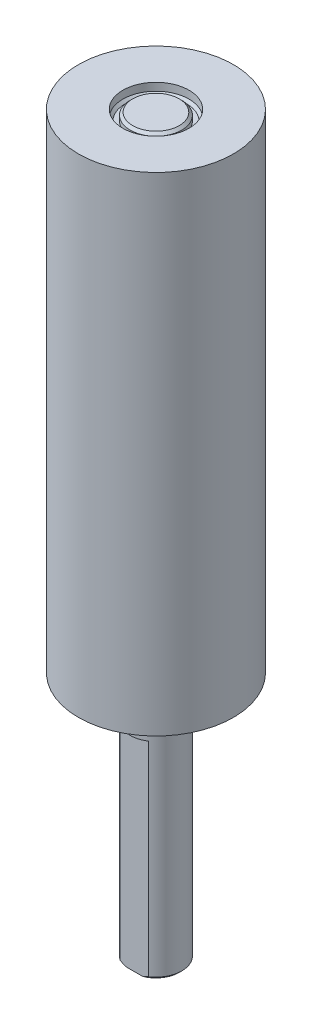
SolidWorks part; units mm, degrees
ref_plane "Alzado" through (0, 0, 0) normal (0, 0, 1) x (1, 0, 0)
ref_plane "Planta" through (0, 0, 0) normal (0, 1, 0) x (1, 0, 0)
ref_plane "Vista lateral" through (0, 0, 0) normal (1, 0, 0) x (0, 0, -1)
ref_plane "Plano4" through (0, 0, 0) normal (0, 0, -1) x (-1, 0, 0)
sketch "Croquis1" plane through (0, 0, 0) normal (0, 0, -1) x (-1, 0, 0)
  line L0 (-7.5, -8) -> (0, -8)
  line L1 (0, -8) -> (0, 39.25)
  line L2 (0, 39.25) -> (-7.5, 39.25)
  line L3 (-7.5, 39.25) -> (-7.5, -8)
  line L4 (0, -8) -> (0, 39.25) construction
revolve "Revolución1" add sketch "Croquis1" angle 360 about L4
sketch "Croquis2" plane through (0, -8, 0) normal (0, -1, 0) x (1, 0, 0)
  circle A0 centre (0, 0) radius 3.2
extrude "Saliente-Extruir1" add sketch "Croquis2" along normal blind 1
sketch "Croquis3" plane through (0, -9, 0) normal (0, -1, 0) x (1, 0, 0)
  circle A0 centre (0, 0) radius 2.5
extrude "Saliente-Extruir2" add sketch "Croquis3" along normal blind 23
sketch "Croquis4" plane through (0, -32, 0) normal (0, -1, 0) x (1, 0, 0)
  line L0 (-1.3565, 2.1) -> (1.3565, 2.1)
  arc A0 (1.3565, 2.1) -> (-1.3565, 2.1) centre (0, 0) ccw
extrude "Cortar-Extruir1" cut sketch "Croquis4" against normal blind 20
hole_wizard "Diámetro de taladro Ø6.4 (6.4)1" positions "Croquis6" profile "Croquis5" hole size "Ø6.4" standard "Ansi Metric"
sketch "Croquis6" plane through (0, 39.25, 0) normal (0, 1, 0) x (1, 0, 0)
  point P0 (0, 0)
sketch "Croquis5" plane through (0, 39.25, 0) normal (1, 0, 0) x (0, 0, 1)
  line L0 (0, 0) -> (0, 1)
  line L1 (0, 1) -> (3.2, 1)
  line L2 (3.2, 1) -> (3.2, 0)
  line L5 (3.2, 0) -> (0, 0)
  line L10 (0, 1) -> (-3.2, 1) construction
  line L11 (0, -6.35) -> (0, 107.95) construction
  dimension "Diámetro de taladro" = 6.4
  dimension "Profundidad de taladro" = 1
  dimension "Ángulo de perforador" = 180
sketch "Croquis7" plane through (0, 0, 0) normal (0, 0, -1) x (-1, 0, 0)
  line L0 (-2.5, 38.25) -> (0, 38.25)
  line L1 (0, 38.25) -> (0, 39)
  line L2 (0, 39) -> (-2.5, 39)
  line L3 (-2.5, 39) -> (-2.5, 38.25)
  line L4 (0, 38.25) -> (0, 39) construction
revolve "Revolución2" add sketch "Croquis7" angle 360 about L4
chamfer "Chaflán1" distance 0.25 angle 45 4 edges at (0, -32, -2.5) (0, -9, -3.2) (0, 39, 2.5) (0, 38.25, 3.2)
